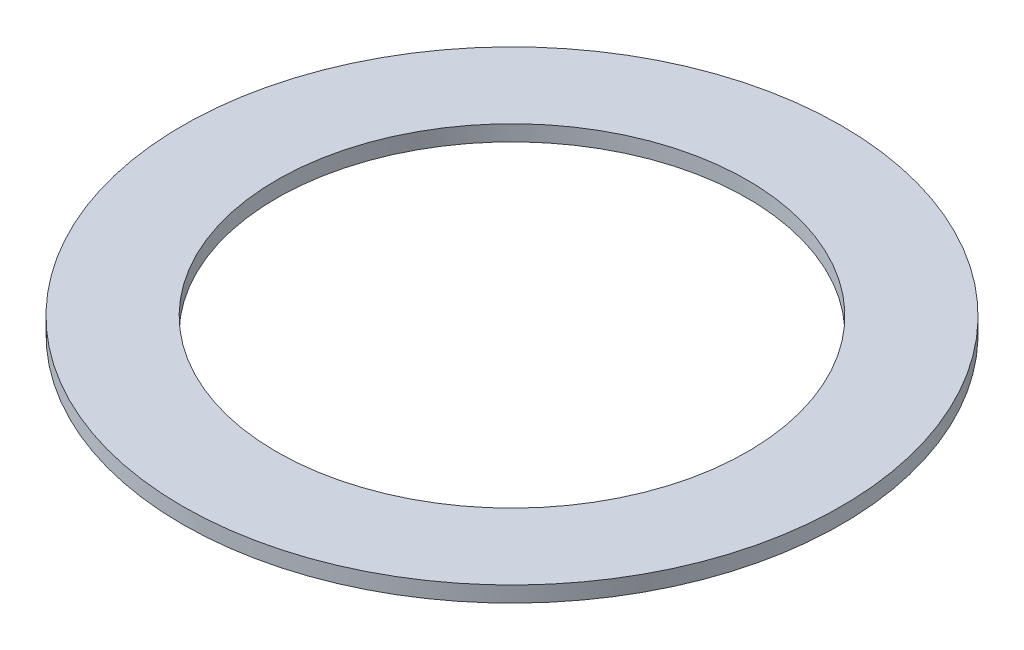
SolidWorks part; units mm, degrees
material "AISI Type A2 Tool Steel"
ref_plane "Front Plane" through (0, 0, 0) normal (0, 0, 1) x (1, 0, 0)
ref_plane "Top Plane" through (0, 0, 0) normal (0, 1, 0) x (1, 0, 0)
ref_plane "Right Plane" through (0, 0, 0) normal (1, 0, 0) x (0, 0, -1)
sketch "Sketch2" plane through (0, 0, 0) normal (0, 1, 0) x (1, 0, 0)
  circle A0 centre (0, 0) radius 21
  circle A1 centre (0, 0) radius 15
  dimension "D1" = 30
  dimension "D2" = 42
extrude "Boss-Extrude1" add sketch "Sketch2" along normal blind 1
